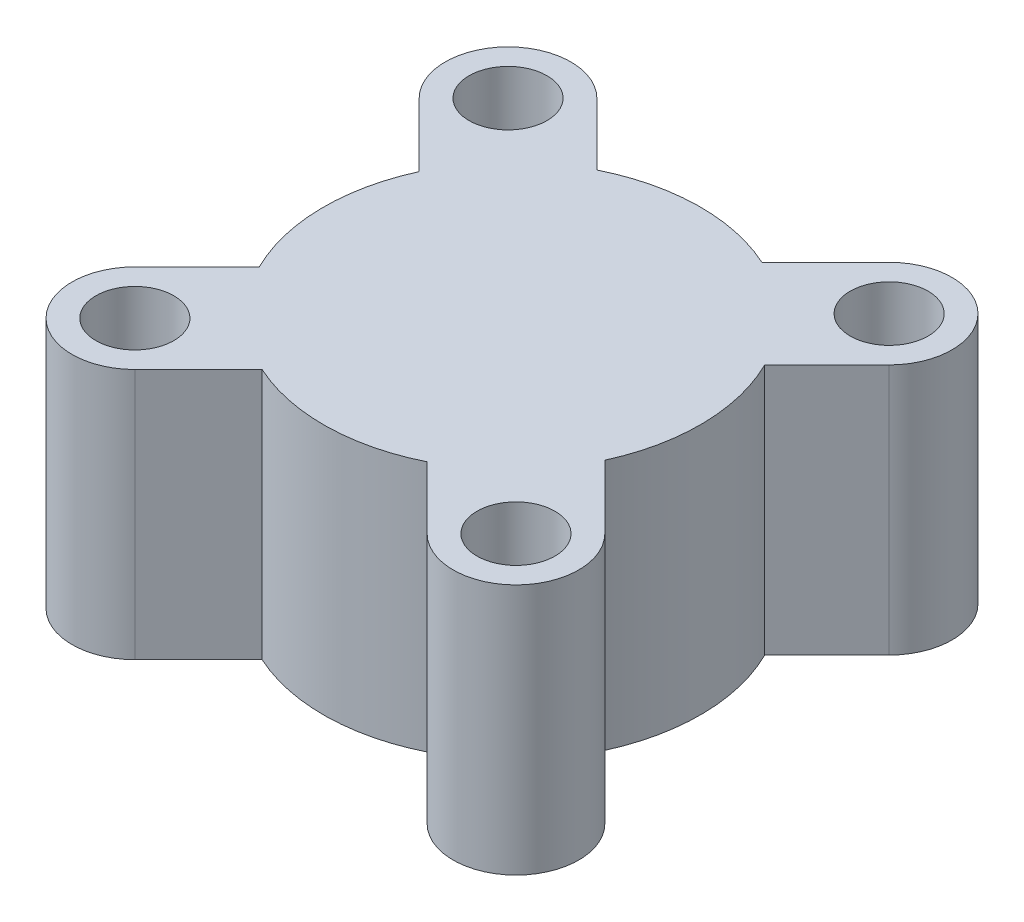
SolidWorks part; units mm, degrees
ref_plane "Front Plane" through (0, 0, 0) normal (0, 0, 1) x (1, 0, 0)
ref_plane "Top Plane" through (0, 0, 0) normal (0, 1, 0) x (1, 0, 0)
ref_plane "Right Plane" through (0, 0, 0) normal (1, 0, 0) x (0, 0, -1)
sketch "Sketch1" plane through (0, 0, 0) normal (0, 1, 0) x (1, 0, 0)
  circle A0 centre (0, 0) radius 7.5
  dimension "D1" = 15
extrude "Boss-Extrude1" add sketch "Sketch1" along normal blind 10
sketch "Sketch3" plane through (0, 0, 0) normal (0, -1, 0) x (1, 0, 0)
  line L4 (-7.4245, 7.5823) -> (0, 0) construction
  line L5 (-7.4245, 7.5823) -> (-5.2472, 5.3588) construction
  line L6 (-7.4245, 7.5823) -> (-5.2472, 5.3588) construction
  line L7 (-5.6575, 9.3508) -> (-3.1232, 6.8188)
  line L8 (-9.1915, 5.8137) -> (-6.7153, 3.3398)
  line L9 (5.8137, 9.1915) -> (3.3398, 6.7153)
  line L10 (9.3508, 5.6575) -> (6.8188, 3.1232)
  line L11 (9.1915, -5.8137) -> (6.7153, -3.3398)
  line L12 (5.6575, -9.3508) -> (3.1232, -6.8188)
  line L13 (-5.8137, -9.1915) -> (-3.3398, -6.7153)
  line L14 (-9.3508, -5.6575) -> (-6.8188, -3.1232)
  arc A0 (-5.6575, 9.3508) -> (-9.1915, 5.8137) centre (-7.4245, 7.5823) ccw
  circle A4 centre (-7.4245, 7.5823) radius 1.55
  arc A6 (-3.1232, 6.8188) -> (-6.7153, 3.3398) centre (0, 0) ccw
  arc A7 (9.3508, 5.6575) -> (5.8137, 9.1915) centre (7.5823, 7.4245) ccw
  circle A8 centre (7.5823, 7.4245) radius 1.55
  arc A9 (6.8188, 3.1232) -> (3.3398, 6.7153) centre (0, 0) ccw
  arc A10 (5.6575, -9.3508) -> (9.1915, -5.8137) centre (7.4245, -7.5823) ccw
  circle A11 centre (7.4245, -7.5823) radius 1.55
  arc A12 (3.1232, -6.8188) -> (6.7153, -3.3398) centre (0, 0) ccw
  arc A13 (-9.3508, -5.6575) -> (-5.8137, -9.1915) centre (-7.5823, -7.4245) ccw
  circle A14 centre (-7.5823, -7.4245) radius 1.55
  arc A15 (-6.8188, -3.1232) -> (-3.3398, -6.7153) centre (0, 0) ccw
  point P0 (0, 0)
  point P1 (0, 0)
  point P11 (0, 0)
  point P33 (0, 0)
  dimension "D3" = 2.5
  dimension "D4" = 3.1
  dimension "D1" = 5
  dimension "D2" = 3.1119
  dimension "D5" = 4
extrude "Boss-Extrude2" add sketch "Sketch3" against normal blind 10
sketch "Sketch4" plane through (0, 0, 0) normal (0, -1, 0) x (1, 0, 0)
  circle A0 centre (0, 0) radius 6.05
  dimension "D1" = 12.1
extrude "Cut-Extrude2" cut sketch "Sketch4" against normal blind 8
